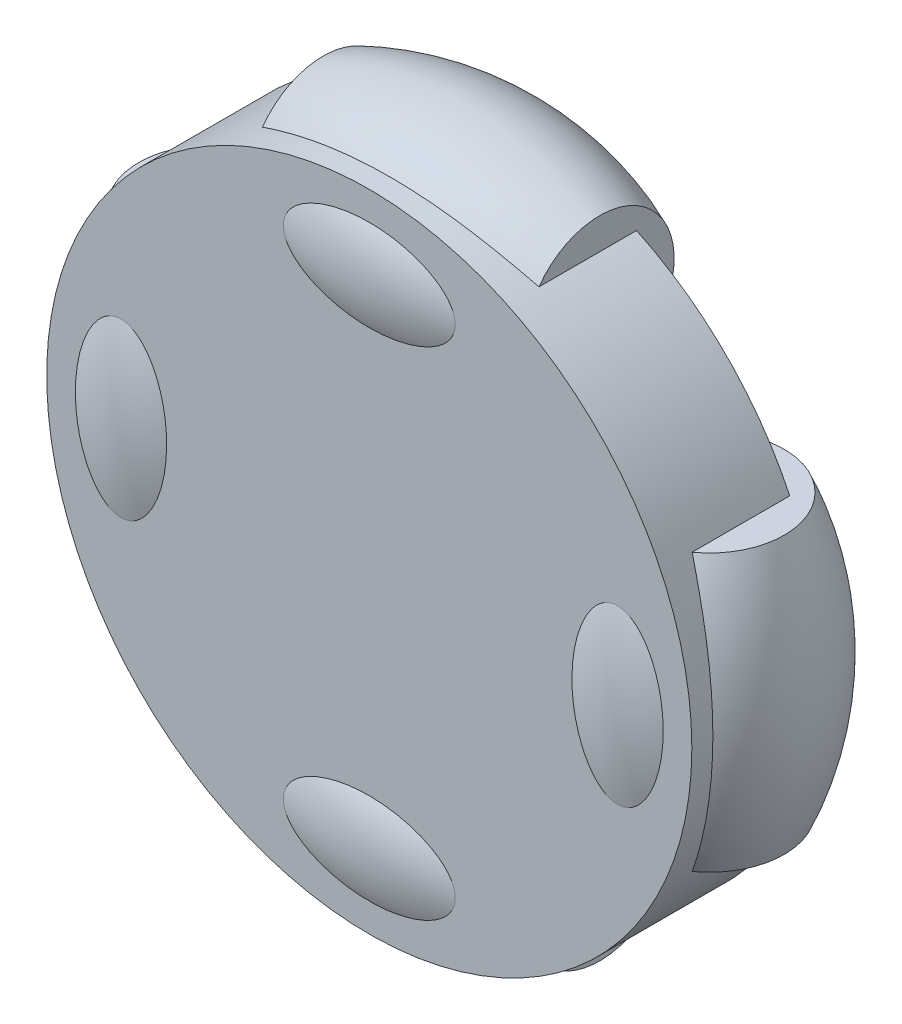
SolidWorks part; units mm, degrees
ref_plane "正面" through (0, 0, 0) normal (0, 0, 1) x (1, 0, 0)
ref_plane "平面" through (0, 0, 0) normal (0, 1, 0) x (1, 0, 0)
ref_plane "右側面" through (0, 0, 0) normal (1, 0, 0) x (0, 0, -1)
sketch "ｽｹｯﾁ1" plane through (0, 0, 0) normal (0, 0, 1) x (1, 0, 0)
  line L0 (0, 0) -> (0, 19.05) construction
  line L1 (-13.4704, 13.4704) -> (13.4704, 13.4704)
  line L2 (-13.4704, 13.4704) -> (-13.4704, -13.4704)
  line L3 (-13.4704, -13.4704) -> (13.4704, -13.4704)
  line L4 (13.4704, 13.4704) -> (13.4704, -13.4704)
  line L5 (-13.4704, 13.4704) -> (13.4704, -13.4704) construction
  line L6 (-13.4704, -13.4704) -> (13.4704, 13.4704) construction
  line L7 (-7.5, 17.5115) -> (-7.5, 9.4293)
  line L8 (7.5, 17.5115) -> (7.5, 9.4293)
  arc A1 (13.4704, 13.4704) -> (-13.4704, 13.4704) centre (0, 0) ccw
  arc A2 (13.4704, 13.4704) -> (-13.4704, 13.4704) centre (0, 26.9408) cw
  dimension "D1" = 38.1
  dimension "D2" = 7.5
revolve "回転1" add sketch "ｽｹｯﾁ1" angle 360 about L1
sketch "ｽｹｯﾁ2" plane through (0, 0, 0) normal (0, 0, 1) x (1, 0, 0)
  circle A0 centre (0, 0) radius 17.5
  dimension "D1" = 35
extrude "ﾎﾞｽ - 押し出し1" add sketch "ｽｹｯﾁ2" along normal blind 5 and the other way blind 2
pattern_circular "円形ﾊﾟﾀｰﾝ1" count 4 over 360 about axis through (0, 0, 0) along (0, 0, 1) of "回転1"
